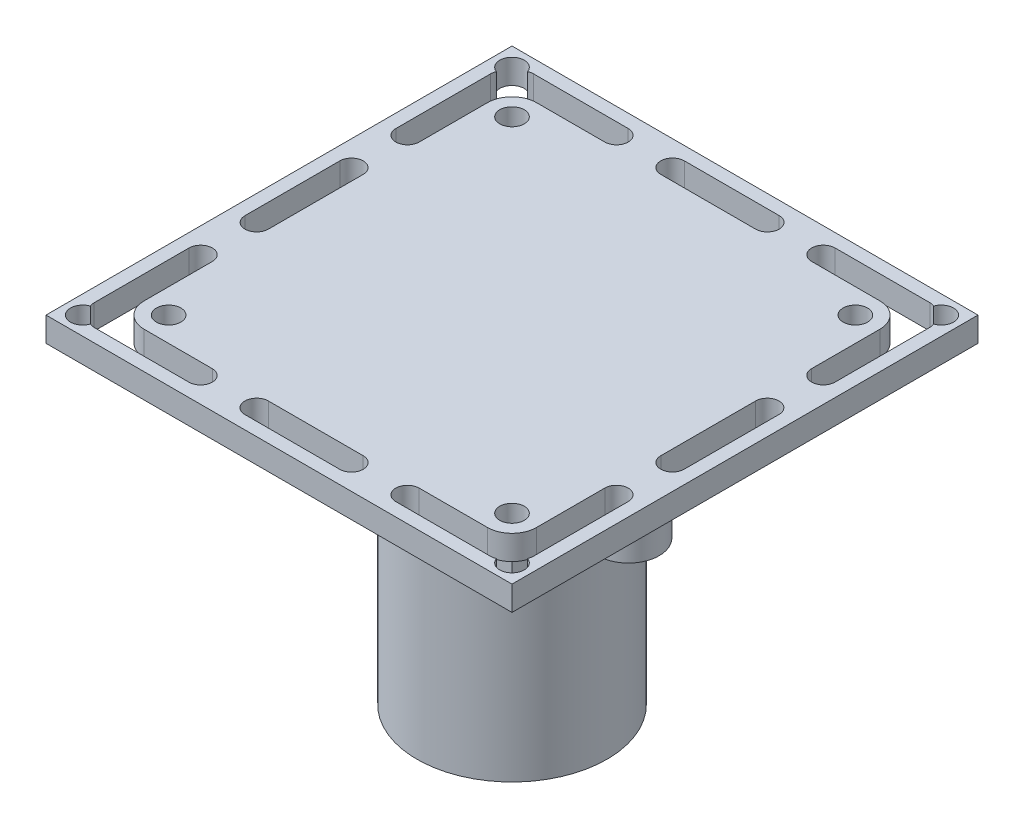
SolidWorks part; units mm, degrees
ref_plane "前视基准面" through (0, 0, 0) normal (0, 0, 1) x (1, 0, 0)
ref_plane "上视基准面" through (0, 0, 0) normal (0, 1, 0) x (1, 0, 0)
ref_plane "右视基准面" through (0, 0, 0) normal (1, 0, 0) x (0, 0, -1)
sketch "草图1" plane through (0, 0, 0) normal (0, 1, 0) x (1, 0, 0)
  line L0 (0, 19) -> (0, -19) construction
  line L1 (-19, 19) -> (19, 19)
  line L2 (-19, 19) -> (-19, -19)
  line L3 (-19, -19) -> (19, -19)
  line L4 (19, 19) -> (19, -19)
  line L5 (-19, 0) -> (19, 0) construction
  line L6 (-16.9541, 3.8665) -> (-16.9541, -3.8665) construction
  line L7 (-4.6584, 17.5) -> (7.6476, 17.5) construction
  line L9 (-7.6476, -17.5) -> (7.6476, -17.5) construction
  line L11 (-14, 16) -> (14, 16)
  line L12 (-16, 14) -> (-16, -14)
  line L13 (-14, -16) -> (14, -16)
  line L14 (16, 14) -> (16, -14)
  line L15 (-15.4142, 15.4142) -> (15.4142, -15.4142) construction
  line L16 (-15.4142, -15.4142) -> (15.4142, 15.4142) construction
  line L21 (-16, 3.8665) -> (-16, -3.8665)
  line L22 (-17.9081, 3.8665) -> (-17.9081, -3.8665)
  line L23 (16, -16) -> (16, -16.0049)
  line L24 (-16, -8.4335) -> (-16, -14)
  line L25 (-17.9081, -8.4335) -> (-17.9081, -16.1665)
  line L26 (-16, -16) -> (-16, -16.0049)
  line L27 (-16, 14) -> (-16, 8.4335)
  line L28 (-17.9081, 16.1665) -> (-17.9081, 8.4335)
  line L30 (16, 14) -> (16, 8.4335)
  line L31 (17.9081, 16.1665) -> (17.9081, 8.4335)
  line L32 (16.9541, 3.8665) -> (16.9541, -3.8665) construction
  line L33 (16, 3.8665) -> (16, -3.8665)
  line L34 (17.9081, 3.8665) -> (17.9081, -3.8665)
  line L35 (-14, 14) -> (14, 14) construction
  line L36 (16, -8.4335) -> (16, -14)
  line L37 (17.9081, -8.4335) -> (17.9081, -16.1665)
  line L38 (-14, 14) -> (-14, -14) construction
  line L39 (-16.1665, -17.9131) -> (-8.4335, -17.9131)
  line L41 (-3.8665, -16.959) -> (3.8665, -16.959) construction
  line L42 (-3.8665, -17.918) -> (3.8665, -17.918)
  line L43 (-3.8665, -16) -> (3.8665, -16)
  line L44 (-14, -14) -> (14, -14) construction
  line L45 (8.4335, -17.9131) -> (16.1665, -17.9131)
  line L47 (14, 14) -> (14, -14) construction
  line L48 (8.4335, 17.9131) -> (16.1665, 17.9131)
  line L50 (-3.8665, 16.959) -> (3.8665, 16.959) construction
  line L51 (-3.8665, 17.918) -> (3.8665, 17.918)
  line L52 (-3.8665, 16) -> (3.8665, 16)
  line L53 (-14, 14) -> (14, -14) construction
  line L54 (-16.1665, 17.9131) -> (-8.4335, 17.9131)
  line L56 (-17.5, 7.651) -> (-17.5, -7.651) construction
  line L57 (17.5, 7.651) -> (17.5, -7.651) construction
  line L58 (-14, -14) -> (14, 14) construction
  arc A0 (-17.8257, -16.5545) -> (-16.556, -17.83) centre (-17.5, -17.5) ccw
  arc A1 (17.8257, -16.5545) -> (16.556, -17.83) centre (17.5, -17.5) cw
  arc A2 (17.8257, 16.5545) -> (16.556, 17.83) centre (17.5, 17.5) ccw
  arc A3 (-17.8257, 16.5545) -> (-16.556, 17.83) centre (-17.5, 17.5) cw
  arc A8 (-16, 3.8665) -> (-17.9081, 3.8665) centre (-16.9541, 3.8665) ccw
  arc A9 (-17.9081, -3.8665) -> (-16, -3.8665) centre (-16.9541, -3.8665) ccw
  arc A10 (-16, -8.4335) -> (-17.9081, -8.4335) centre (-16.9541, -8.4335) ccw
  arc A11 (-17.9081, -16.1665) -> (-17.8257, -16.5545) centre (-16.9541, -16.1665) ccw
  arc A12 (-17.8257, 16.5545) -> (-17.9081, 16.1665) centre (-16.9541, 16.1665) ccw
  arc A13 (-17.9081, 8.4335) -> (-16, 8.4335) centre (-16.9541, 8.4335) ccw
  arc A15 (17.9081, 8.4335) -> (16, 8.4335) centre (16.9541, 8.4335) cw
  arc A16 (16, 3.8665) -> (17.9081, 3.8665) centre (16.9541, 3.8665) cw
  arc A17 (17.9081, -3.8665) -> (16, -3.8665) centre (16.9541, -3.8665) cw
  arc A18 (16, -8.4335) -> (17.9081, -8.4335) centre (16.9541, -8.4335) cw
  arc A19 (17.9081, -16.1665) -> (17.8257, -16.5545) centre (16.9541, -16.1665) cw
  arc A20 (-16.1665, -17.9131) -> (-16.556, -17.83) centre (-16.1665, -16.959) cw
  arc A21 (-8.4335, -16.0049) -> (-8.4335, -17.9131) centre (-8.4335, -16.959) cw
  arc A22 (-3.8665, -17.918) -> (-3.8665, -16) centre (-3.8665, -16.959) cw
  arc A23 (3.8665, -16) -> (3.8665, -17.918) centre (3.8665, -16.959) cw
  arc A24 (8.4335, -17.9131) -> (8.4335, -16.0049) centre (8.4335, -16.959) cw
  arc A26 (8.4335, 17.9131) -> (8.4335, 16.0049) centre (8.4335, 16.959) ccw
  arc A28 (-3.8665, 17.918) -> (-3.8665, 16) centre (-3.8665, 16.959) ccw
  arc A29 (3.8665, 16) -> (3.8665, 17.918) centre (3.8665, 16.959) ccw
  arc A30 (-16.1665, 17.9131) -> (-16.556, 17.83) centre (-16.1665, 16.959) ccw
  arc A31 (-8.4335, 16) -> (-8.4335, 17.9131) centre (-8.4335, 16.9565) ccw
  arc A32 (16.556, 17.83) -> (16.1665, 17.9131) centre (16.1665, 16.959) ccw
  arc A33 (17.8257, 16.5545) -> (17.9081, 16.1665) centre (16.9541, 16.1665) cw
  arc A34 (-14, 16) -> (-16, 14) centre (-14, 14) ccw
  arc A35 (16.556, -17.83) -> (16.1665, -17.9131) centre (16.1665, -16.959) cw
  arc A36 (14, 16) -> (16, 14) centre (14, 14) cw
  arc A37 (14, -16) -> (16, -14) centre (14, -14) ccw
  arc A38 (-16, -14) -> (-14, -16) centre (-14, -14) ccw
  circle A39 centre (-14, -14) radius 1
  circle A40 centre (14, -14) radius 1
  circle A41 centre (14, 14) radius 1
  circle A42 centre (-14, 14) radius 1
  point P0 (0, 0)
  point P6 (0, 0)
  point P15 (0, 0)
  point P16 (0, 0)
  point P27 (-16.9541, 0)
  point P36 (-16.9541, -12.3)
  point P43 (-16.9541, 12.3)
  point P48 (16.9541, 12.3)
  point P55 (16.9541, 0)
  point P62 (16.9541, -12.3)
  point P69 (-12.3, -16.959)
  point P76 (0, -16.959)
  point P83 (12.3, -16.959)
  point P90 (12.3, 16.959)
  point P97 (0, 16.959)
  point P104 (-12.3, 16.959)
  point P111 (0, 0)
  dimension "D6" = 2
  dimension "D7" = 2
  dimension "D8" = 2
  dimension "D1" = 38
  dimension "D2" = 38
  dimension "D3" = 35
  dimension "D4" = 28
  dimension "D5" = 32
extrude "凸台-拉伸1" add sketch "草图1" along normal blind 2
sketch "草图2" plane through (0, 2, 0) normal (0, 1, 0) x (1, 0, 0)
  line L0 (-17.9081, -16.1665) -> (-17.9081, -8.4335)
  line L1 (-16, -8.4335) -> (-16, -14)
  line L2 (-14, -16) -> (-8.4335, -16.0049)
  line L3 (-8.4335, -17.9131) -> (-16.1665, -17.9131)
  line L4 (0, -19) -> (0, 19) construction
  line L5 (17.9081, -16.1665) -> (17.9081, -8.4335)
  line L6 (16, -8.4335) -> (16, -14)
  line L7 (14, -16) -> (8.4335, -16.0049)
  line L8 (8.4335, -17.9131) -> (16.1665, -17.9131)
  line L9 (-19, 0) -> (19, 0) construction
  line L10 (8.4335, 17.9131) -> (16.1665, 17.9131)
  line L11 (14, 16) -> (8.4335, 16.0049)
  line L12 (16, 8.4335) -> (16, 14)
  line L13 (17.9081, 16.1665) -> (17.9081, 8.4335)
  line L14 (-8.4335, 17.9131) -> (-16.1665, 17.9131)
  line L15 (-14, 16) -> (-8.4335, 16.0049)
  line L16 (-16, 8.4335) -> (-16, 14)
  line L17 (-17.9081, 16.1665) -> (-17.9081, 8.4335)
  arc A0 (-17.8257, -16.5545) -> (-16.556, -17.83) centre (-17.5, -17.5) ccw
  arc A1 (-17.9081, -8.4335) -> (-16, -8.4335) centre (-16.9541, -8.4335) cw
  arc A2 (-16, -14) -> (-14, -16) centre (-14, -14) ccw
  arc A3 (-8.4335, -16.0049) -> (-8.4335, -17.9131) centre (-8.4343, -16.959) cw
  arc A4 (-16.1665, -17.9131) -> (-16.556, -17.83) centre (-16.1665, -16.959) cw
  arc A5 (-17.9081, -16.1665) -> (-17.8257, -16.5545) centre (-16.9541, -16.1665) ccw
  arc A6 (17.9081, -16.1665) -> (17.8257, -16.5545) centre (16.9541, -16.1665) cw
  arc A7 (17.9081, -8.4335) -> (16, -8.4335) centre (16.9541, -8.4335) ccw
  arc A8 (8.4335, -16.0049) -> (8.4335, -17.9131) centre (8.4343, -16.959) ccw
  arc A9 (16.1665, -17.9131) -> (16.556, -17.83) centre (16.1665, -16.959) ccw
  arc A10 (17.8257, -16.5545) -> (16.556, -17.83) centre (17.5, -17.5) cw
  arc A11 (16, -14) -> (14, -16) centre (14, -14) cw
  arc A12 (16, 14) -> (14, 16) centre (14, 14) ccw
  arc A13 (17.8257, 16.5545) -> (16.556, 17.83) centre (17.5, 17.5) ccw
  arc A14 (16.1665, 17.9131) -> (16.556, 17.83) centre (16.1665, 16.959) cw
  arc A15 (8.4335, 16.0049) -> (8.4335, 17.9131) centre (8.4343, 16.959) cw
  arc A16 (17.9081, 8.4335) -> (16, 8.4335) centre (16.9541, 8.4335) cw
  arc A17 (17.9081, 16.1665) -> (17.8257, 16.5545) centre (16.9541, 16.1665) ccw
  arc A18 (-17.9081, 16.1665) -> (-17.8257, 16.5545) centre (-16.9541, 16.1665) cw
  arc A19 (-16.1665, 17.9131) -> (-16.556, 17.83) centre (-16.1665, 16.959) ccw
  arc A20 (-8.4335, 16.0049) -> (-8.4335, 17.9131) centre (-8.4343, 16.959) ccw
  arc A21 (-16, 14) -> (-14, 16) centre (-14, 14) cw
  arc A22 (-17.9081, 8.4335) -> (-16, 8.4335) centre (-16.9541, 8.4335) ccw
  arc A23 (-17.8257, 16.5545) -> (-16.556, 17.83) centre (-17.5, 17.5) cw
extrude "切除-拉伸1" cut sketch "草图2" against normal through all
sketch "草图3" plane through (0, 0, 0) normal (0, -1, 0) x (1, 0, 0)
  line L0 (-8.5, 2.5) -> (-9.5, 2.5)
  line L1 (-8.5, 8.5) -> (8.5, 8.5)
  line L2 (-8.5, 8.5) -> (-8.5, 2.5)
  line L3 (-8.5, -8.5) -> (8.5, -8.5)
  line L4 (8.5, 8.5) -> (8.5, 2.5)
  line L5 (-8.5, 8.5) -> (8.5, -8.5) construction
  line L6 (-8.5, -8.5) -> (8.5, 8.5) construction
  line L7 (-9.5, -2.5) -> (-8.5, -2.5)
  line L8 (0, 0) -> (-22.4682, 0) construction
  line L9 (-8.5, -2.5) -> (-8.5, -8.5)
  line L10 (0, 0) -> (0, 5.1642) construction
  line L11 (9.5, -2.5) -> (8.5, -2.5)
  line L12 (8.5, 2.5) -> (9.5, 2.5)
  line L13 (8.5, -2.5) -> (8.5, -8.5)
  arc A0 (-9.5, 2.5) -> (-9.5, -2.5) centre (-9.5, 0) ccw
  arc A1 (9.5, 2.5) -> (9.5, -2.5) centre (9.5, 0) cw
  point P0 (0, 0)
  point P13 (-9, -2.5)
  point P14 (9, -2.5)
  dimension "D4" = 2.5
  dimension "D1" = 17
  dimension "D2" = 17
  dimension "D3" = 1
extrude "凸台-拉伸2" add sketch "草图3" along normal blind 9
sketch "草图4" plane through (0, -9, 0) normal (0, -1, 0) x (1, 0, 0)
  circle A0 centre (0, 0) radius 7.75
  dimension "D1" = 15.5
extrude "凸台-拉伸3" add sketch "草图4" along normal blind 16.5
